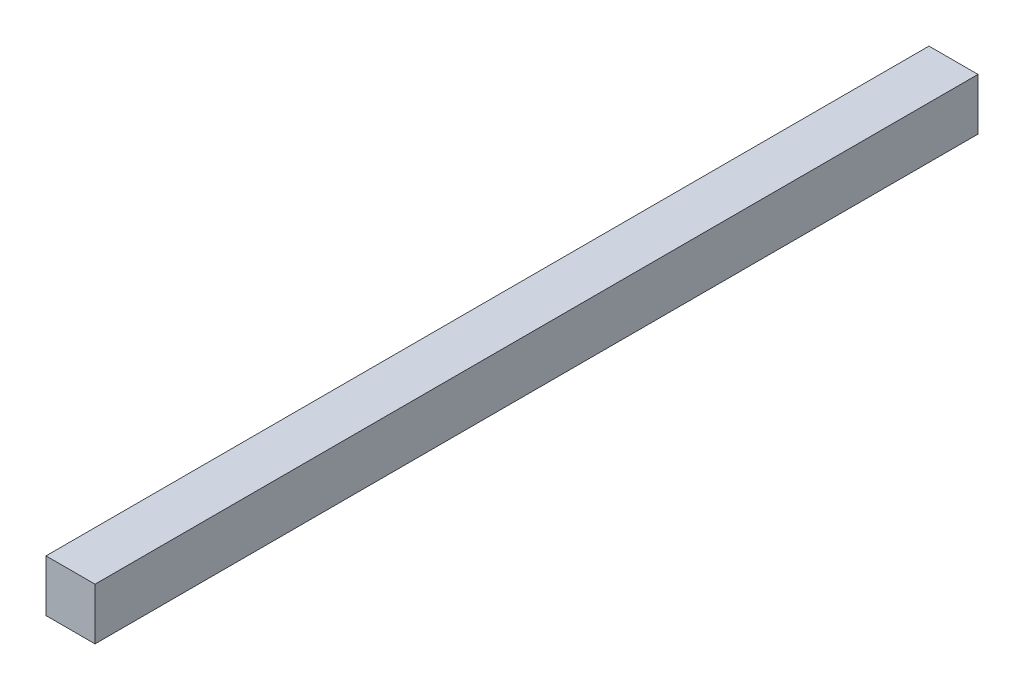
SolidWorks part; units mm, degrees
ref_plane "前视基准面" through (0, 0, 0) normal (0, 0, 1) x (1, 0, 0)
ref_plane "上视基准面" through (0, 0, 0) normal (0, 1, 0) x (1, 0, 0)
ref_plane "右视基准面" through (0, 0, 0) normal (1, 0, 0) x (0, 0, -1)
other "Configuration Table"
sketch "草图1" plane through (0, 0, 0) normal (0, 0, 1) x (1, 0, 0)
  line L1 (-4.8327, -5.0999) -> (4.8327, -5.0999)
  line L2 (-4.8327, -5.0999) -> (-4.8327, 5.0999)
  line L3 (-4.8327, 5.0999) -> (4.8327, 5.0999)
  line L4 (4.8327, -5.0999) -> (4.8327, 5.0999)
  line L5 (-4.8327, -5.0999) -> (4.8327, 5.0999) construction
  line L6 (-4.8327, 5.0999) -> (4.8327, -5.0999) construction
  point P0 (0, 0)
extrude "凸台-拉伸2" add sketch "草图1" along normal blind 100 and the other way blind 74.1
